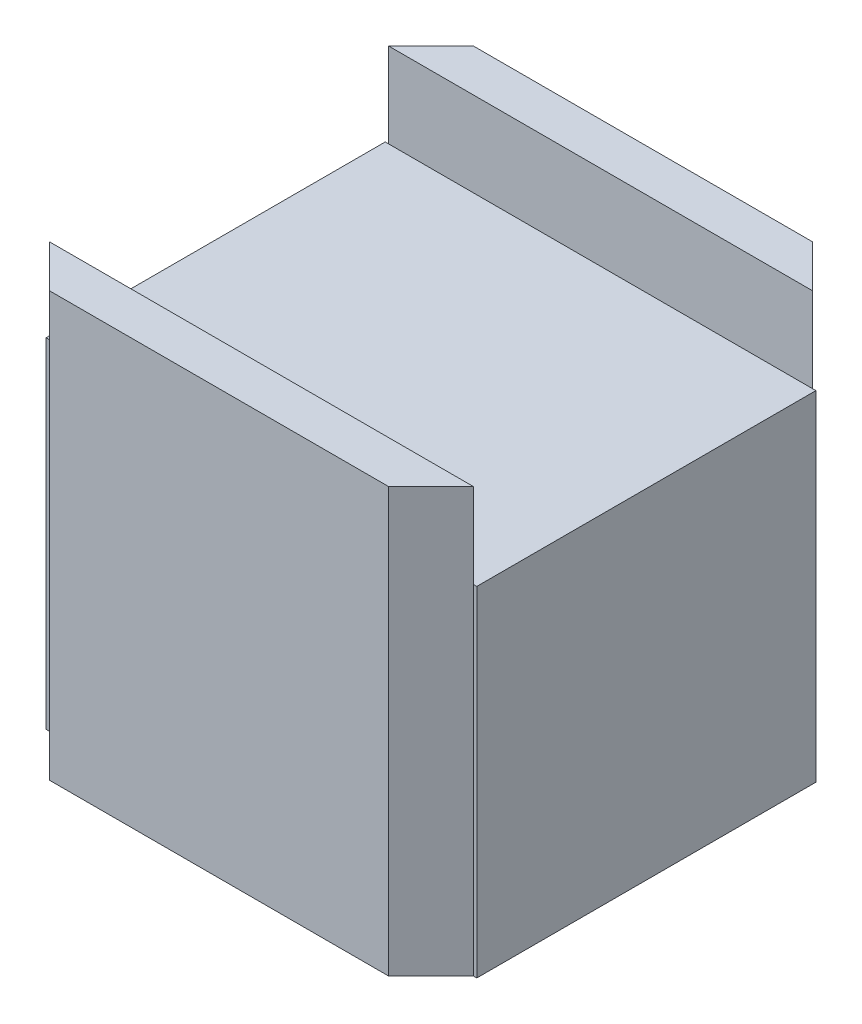
SolidWorks part; units mm, degrees
ref_plane "Спереди" through (0, 0, 0) normal (0, 0, 1) x (1, 0, 0)
ref_plane "Сверху" through (0, 0, 0) normal (0, 1, 0) x (1, 0, 0)
ref_plane "Справа" through (0, 0, 0) normal (1, 0, 0) x (0, 0, -1)
sketch "Эскиз1" plane through (0, 0, 0) normal (0, 1, 0) x (1, 0, 0)
  line L0 (-9.6951, 0) -> (11.3637, 0) construction
  line L1 (-1.25, 1) -> (-1, 1.25)
  line L2 (0, 10.4719) -> (0, -10.0116) construction
  line L3 (-1, 1.25) -> (1, 1.25)
  line L4 (-1.25, 1) -> (-1.25, -1)
  line L5 (-1, -1.25) -> (1, -1.25)
  line L6 (1.25, 1) -> (1.25, -1)
  line L7 (-1.25, 1.25) -> (1.25, -1.25) construction
  line L8 (-1.25, -1.25) -> (1.25, 1.25) construction
  line L9 (1, 1.25) -> (1.25, 1)
  line L10 (1, -1.25) -> (1.25, -1)
  line L11 (-1.25, -1) -> (-1, -1.25)
  line L13 (-1.27, 1) -> (1.27, 1)
  line L14 (-1.27, 1) -> (-1.27, -1)
  line L15 (-1.27, -1) -> (1.27, -1)
  line L16 (1.27, 1) -> (1.27, -1)
  line L17 (-1.27, 1) -> (1.27, -1) construction
  line L18 (-1.27, -1) -> (1.27, 1) construction
  point P4 (0, 0)
  point P18 (0, 0)
  dimension "D1" = 2.5
  dimension "D2" = 0.02
extrude "Бобышка-Вытянуть1" add sketch "Эскиз1" along normal blind 2.5 contours L14 L15 L4 L13 | L4 L15 L6 L13 | L1 L13 L9 L3 | L16 L13 L6 L15 | L15 L11 L5 L10
sketch "Эскиз2" plane through (0, 2.5, 0) normal (0, 1, 0) x (1, 0, 0)
  line L6 (-1.27, -1) -> (1.27, -1)
  line L8 (-1.27, -1) -> (-1.27, 1)
  line L9 (-1.27, 1) -> (1.27, 1)
  line L10 (1.27, -1) -> (1.27, 1)
  line L11 (-1.27, -1) -> (1.27, 1) construction
  line L12 (-1.27, 1) -> (1.27, -1) construction
  point P0 (0, 0)
extrude "Вырез-Вытянуть1" cut sketch "Эскиз2" against normal blind 0.5
sketch "Эскиз4" plane through (0, 0, 0) normal (1, 0, 0) x (0, 0, -1)
  line L0 (0, 0) -> (0, 2.5) construction
  line L1 (-1, 2.5) -> (-1.25, 2.5) construction
